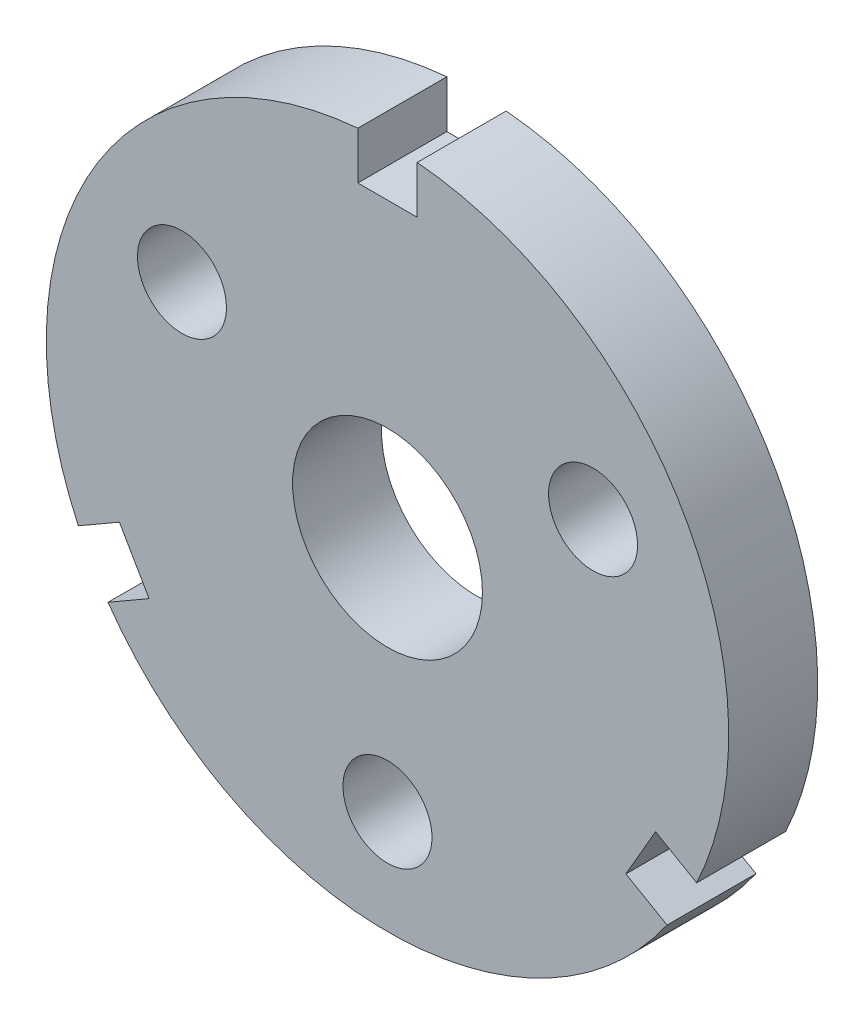
SolidWorks part; units mm, degrees
ref_plane "Front Plane" through (0, 0, 0) normal (0, 0, 1) x (1, 0, 0)
ref_plane "Top Plane" through (0, 0, 0) normal (0, 1, 0) x (1, 0, 0)
ref_plane "Right Plane" through (0, 0, 0) normal (1, 0, 0) x (0, 0, -1)
sketch "Sketch1" plane through (0, 0, 0) normal (0, 0, 1) x (1, 0, 0)
  line L0 (0, 0) -> (-16, 0) construction
  line L1 (0, 0) -> (-34.641, 20) construction
  line L3 (-5, 57.2822) -> (-5, 49.2822)
  line L4 (5, 57.2822) -> (5, 49.2822)
  line L5 (5, 49.2822) -> (-5, 49.2822)
  line L6 (0, 57.5) -> (0, 49.2822) construction
  line L7 (0, 0) -> (0, 10.5287) construction
  line L8 (0, 0) -> (0, -56.3881) construction
  line L9 (0, 0) -> (-49.7845, 28.7706) construction
  line L10 (0, 0) -> (49.7965, 28.75) construction
  line L11 (-47.1078, -32.9712) -> (-40.1796, -28.9712)
  line L12 (-40.1796, -28.9712) -> (-45.1796, -20.311)
  line L13 (-52.1078, -24.311) -> (-45.1796, -20.311)
  line L14 (52.1078, -24.311) -> (45.1796, -20.311)
  line L15 (45.1796, -20.311) -> (40.1796, -28.9712)
  line L16 (47.1078, -32.9712) -> (40.1796, -28.9712)
  line L17 (-5, 57.2822) -> (5, 57.2822)
  circle A0 centre (0, 0) radius 16
  arc A1 (-5, 57.2822) -> (5, 57.2822) centre (0, 0) ccw
  circle A2 centre (0, 0) radius 40 construction
  circle A3 centre (-34.641, 20) radius 7.5
  circle A4 centre (0, -40) radius 7.5
  circle A5 centre (34.641, 20) radius 7.5
  point P9 (0, 57.5)
  dimension "D1" = 32
  dimension "D2" = 115
  dimension "D6" = 80
  dimension "D7" = 15
  dimension "D8" = 15
  dimension "D3" = 120
  dimension "D4" = 10
  dimension "D5" = 8
  dimension "D9" = 120
extrude "Boss-Extrude1" add sketch "Sketch1" along normal blind 15
